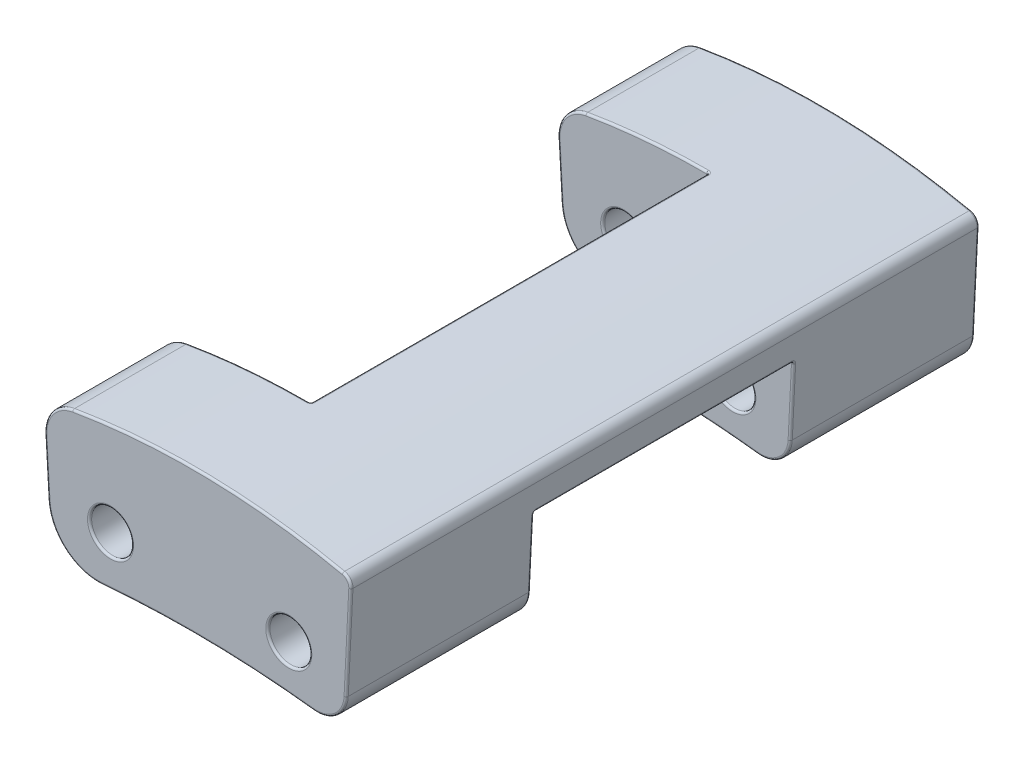
SolidWorks part; units mm, degrees
ref_plane "Front Plane" through (0, 0, 0) normal (0, 0, 1) x (1, 0, 0)
ref_plane "Top Plane" through (0, 0, 0) normal (0, 1, 0) x (1, 0, 0)
ref_plane "Right Plane" through (0, 0, 0) normal (1, 0, 0) x (0, 0, -1)
sketch "Sketch1" plane through (0, 0, 0) normal (0, 0, 1) x (1, 0, 0)
  line L0 (3.2145, 1.1802) -> (3.1395, -0.1311)
  line L1 (-3.7507, -0.1311) -> (-3.8257, 1.1802)
  arc A0 (-3.1613, 2.0145) -> (-3.8257, 1.1802) centre (-3.027, 1.2258) ccw
  arc A1 (2.5502, 2.0145) -> (-3.1613, 2.0145) centre (-0.3056, -14.744) ccw
  arc A2 (3.2145, 1.1802) -> (2.5502, 2.0145) centre (2.4158, 1.2258) ccw
  arc A3 (-3.7507, -0.1311) -> (-2.4498, -1.2582) centre (-2.5527, -0.0627) ccw
  arc A4 (1.8386, -1.2582) -> (-2.4498, -1.2582) centre (-0.3056, -26.1661) ccw
  arc A5 (1.8386, -1.2582) -> (3.1395, -0.1311) centre (1.9415, -0.0627) ccw
  circle A6 centre (-2.2556, -0.0709) radius 0.5
extrude "Boss-Extrude1" add sketch "Sketch1" along normal mid plane 15
sketch "Sketch2" plane through (0, 0, 7.5) normal (0, 0, 1) x (1, 0, 0)
  line L0 (1.8386, -1.2582) -> (2.0484, 3.0041)
  line L1 (2.0484, 3.0041) -> (6.0439, 1.739)
  line L2 (6.0439, 1.739) -> (3.826, -1.9442)
  line L3 (3.826, -1.9442) -> (1.8386, -1.2582)
extrude "Cut-Extrude1" cut sketch "Sketch2" against normal blind 15
sketch "Sketch3" plane through (0, 0, 0) normal (0, 1, 0) x (1, 0, 0)
  line L0 (-2.7216, 0) -> (2.7216, 0) construction
  line L1 (-6.7347, 4.75) -> (-0.227, 4.75)
  line L2 (-6.7347, 4.75) -> (-6.7347, -4.75)
  line L3 (-6.7347, -4.75) -> (-0.227, -4.75)
  line L4 (-0.227, 4.75) -> (-0.227, -4.75)
  line L5 (-3.827, 7.5) -> (-3.827, -7.5) construction
  dimension "D1" = 9.5
  dimension "D2" = 4.75
  dimension "D3" = 3.6
extrude "Cut-Extrude2" cut sketch "Sketch3" against normal mid plane 10
sketch "Sketch4" plane through (1.8959, -0.0934, 0) normal (0.9988, -0.0492, 0) x (0, 0, -1)
  line L4 (-7.5, 2.1945) -> (-7.5, -1.1663)
  line L5 (-7.5, -1.1663) -> (7.5, -1.1663)
  line L6 (7.5, -1.1663) -> (7.5, 2.1945)
  line L7 (7.5, 2.1945) -> (-7.5, 2.1945)
  line L8 (-7.5, 2.1945) -> (-7.5, -1.1663)
  line L9 (-7.5, -1.1663) -> (7.5, -1.1663)
  line L10 (7.5, -1.1663) -> (7.5, 2.1945)
  line L11 (7.5, 2.1945) -> (-7.5, 2.1945)
  dimension "D1" = 0
extrude "Boss-Extrude2" add sketch "Sketch4" along normal blind 1.5
sketch "Sketch5" plane through (0, 0, 7.5) normal (0, 0, 1) x (1, 0, 0)
  line L4 (1.8386, -1.2582) -> (3.3368, -1.332)
  line L5 (3.3368, -1.332) -> (3.502, 2.0247)
  line L6 (3.502, 2.0247) -> (2.0038, 2.0984)
  line L7 (-3.8257, 1.1802) -> (-3.7507, -0.1311)
  line L9 (3.4923, 1.8264) -> (3.502, 2.0247)
  line L11 (-3.8257, 1.1802) -> (-3.7507, -0.1311)
  arc A4 (1.8386, -1.2582) -> (-2.4498, -1.2582) centre (-0.3056, -26.1661) ccw
  arc A5 (2.0038, 2.0984) -> (-3.1613, 2.0145) centre (-0.3056, -14.744) ccw
  arc A6 (-3.1613, 2.0145) -> (-3.8257, 1.1802) centre (-3.027, 1.2258) ccw
  arc A7 (-3.7507, -0.1311) -> (-2.4498, -1.2582) centre (-2.5527, -0.0627) ccw
  arc A8 (4.8539, -1.7043) -> (-2.4498, -1.2582) centre (-0.3056, -26.1661) ccw
  arc A9 (4.2803, 1.6258) -> (-3.1613, 2.0145) centre (-0.3056, -14.744) ccw
  arc A10 (-3.1613, 2.0145) -> (-3.8257, 1.1802) centre (-3.027, 1.2258) ccw
  arc A11 (-3.7507, -0.1311) -> (-2.4498, -1.2582) centre (-2.5527, -0.0627) ccw
  dimension "D1" = 0
sketch "Sketch6" plane through (0, 0, 7.5) normal (0, 0, 1) x (1, 0, 0)
  line L0 (-3.1613, 2.0145) -> (3.5829, 4.0791)
  line L1 (3.5829, 4.0791) -> (5.2679, 2.2022)
  line L2 (5.2679, 2.2022) -> (4.2803, 1.6258)
  arc A0 (4.2803, 1.6258) -> (-3.1613, 2.0145) centre (-0.3056, -14.744) ccw construction
  arc A1 (4.2803, 1.6258) -> (-3.1613, 2.0145) centre (-0.3056, -14.744) ccw
extrude "Cut-Extrude3" cut sketch "Sketch6" against normal through all
sketch "Sketch7" plane through (0, 0, 7.5) normal (0, 0, 1) x (1, 0, 0)
  line L0 (3.379, -0.4744) -> (3.3368, -1.332)
  line L1 (3.4923, 1.8264) -> (3.3368, -1.332) construction
  line L2 (3.3368, -1.332) -> (3.3318, -1.4322)
  line L3 (3.379, -0.4744) -> (0.7899, -1.1901)
  arc A0 (4.8539, -1.7043) -> (-2.4498, -1.2582) centre (-0.3056, -26.1661) ccw construction
  arc A1 (3.3318, -1.4322) -> (0.7899, -1.1901) centre (-0.3056, -26.1661) ccw
extrude "Boss-Extrude3" add sketch "Sketch7" against normal up to surface (15 mm away)
sketch "Sketch8" plane through (0, 0, 7.5) normal (0, 0, 1) x (1, 0, 0)
  line L0 (4.0309, 0) -> (-4.0309, 0) construction
  line L1 (0, -1.9734) -> (0, 1.9734) construction
  circle A0 centre (2, -0.2) radius 0.5
  dimension "D1" = 1
  dimension "D3" = 2
  dimension "D2" = 0.2
extrude "Cut-Extrude4" cut sketch "Sketch8" against normal through all
fillet "Fillet1" radius 0.25 1 edges at (3.4923, 1.8264, 0)
fillet "Fillet2" radius 0.7 1 edges at (3.3318, -1.4322, 0)
sketch "Sketch9" plane through (0, 0, 0) normal (0, 1, 0) x (1, 0, 0)
  line L0 (-1.9773, 0) -> (1.9773, 0) construction
  line L1 (1.1353, 3.1) -> (8.6305, 3.1)
  line L2 (1.1353, 3.1) -> (1.1353, -3.1)
  line L3 (1.1353, -3.1) -> (8.6305, -3.1)
  line L4 (8.6305, 3.1) -> (8.6305, -3.1)
  dimension "D1" = 6.2
  dimension "D2" = 3.1
extrude "Cut-Extrude5" cut sketch "Sketch9" against normal blind 2 and the other way blind 1
fillet "Fillet3" radius 0.05 51 edges at (1.1353, -1.2077, 0) (3.4516, 1, 0) (3.1225, -1.1731, 3.1) (3.1225, -1.1731, -3.1) (3.1225, -1.1731, -7.5) (3.1225, -1.1731, 7.5) (3.4306, 1.7803, 7.5) (3.4306, 1.7803, -7.5) (-0.227, -1.1662, 0) (0.0715, -1.169, 7.5) (0.0715, -1.169, -7.5) (-3.3384, -0.9696, 4.75) (-3.3384, -0.9696, 7.5) (-3.3384, -0.9696, -4.75) (-3.3384, -0.9696, -7.5) (-3.7882, 0.5245, 4.75) (-3.7882, 0.5245, 7.5) (-3.7882, 0.5245, -4.75) (-3.7882, 0.5245, -7.5) (-3.6528, 1.7242, 4.75) (-3.6528, 1.7242, 7.5) (-3.6528, 1.7242, -4.75) (-3.6528, 1.7242, -7.5) (0.0686, 2.2519, 7.5) (0.0686, 2.2519, -7.5) (-1.7556, -0.0709, 4.75) (-1.7556, -0.0709, 7.5) (-2.7556, -0.0709, -4.75) (-1.7556, -0.0709, -7.5) (-0.227, 2.2559, 0) (-1.6994, 2.1988, -4.75) (-1.3394, -1.1875, -4.75) (-1.6994, 2.1988, 4.75) (-1.3394, -1.1875, 4.75) (-0.227, 0.5448, -4.75) (-0.227, 0.5448, 4.75) (3.4255, 0.4712, -7.5) (3.4255, 0.4712, 7.5) (2.5, -0.2, -7.5) (2.5, -0.2, -3.1) (2.5, -0.2, 7.5) (1.5, -0.2, 3.1) (1.8631, -1.2604, 3.1) (3.4104, 0.1633, 3.1) (1.8631, -1.2604, -3.1) (3.4104, 0.1633, -3.1) (1.1353, -0.1038, 3.1) (1.1353, -0.1038, -3.1) (2.2934, 1, -3.1) (2.2934, 1, 3.1) (1.1353, 1, 0)
